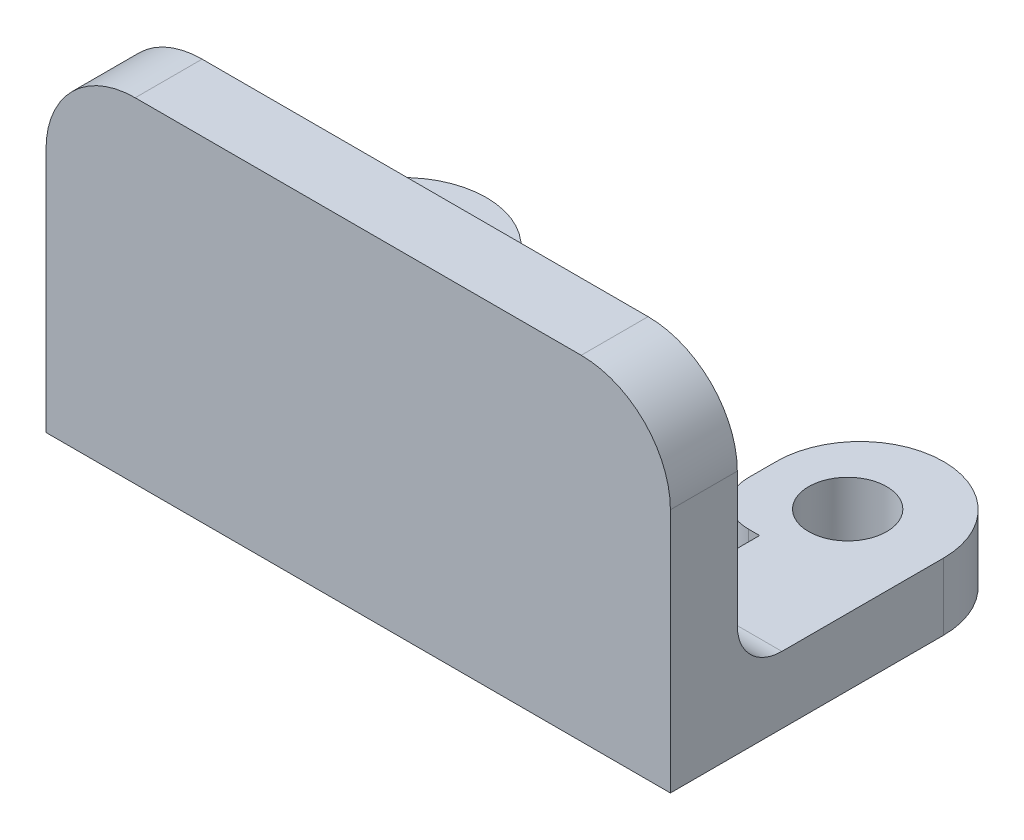
SolidWorks part; units mm, degrees
material "PP Copolymer"
ref_plane "Alzado" through (0, 0, 0) normal (0, 0, 1) x (1, 0, 0)
ref_plane "Planta" through (0, 0, 0) normal (0, 1, 0) x (1, 0, 0)
ref_plane "Vista lateral" through (0, 0, 0) normal (1, 0, 0) x (0, 0, -1)
sketch "Croquis2" plane through (0, 0, 0) normal (1, 0, 0) x (0, 0, -1)
  line L1 (-3, 1.5) -> (8, 1.5)
  line L2 (-8, 1.5) -> (-8, -1.5)
  line L3 (-8, -1.5) -> (8, -1.5)
  line L4 (8, 1.5) -> (8, -1.5)
  line L5 (-8, 1.5) -> (8, -1.5) construction
  line L6 (-8, -1.5) -> (8, 1.5) construction
  line L8 (-8, 1.5) -> (-8, 13.5)
  line L9 (-8, 13.5) -> (-5, 13.5)
  line L10 (-5, 3.5) -> (-5, 13.5)
  arc A0 (-5, 3.5) -> (-3, 1.5) centre (-3, 3.5) ccw
  point P0 (0, 0)
  dimension "D3" = 2
  dimension "D1" = 16
  dimension "D2" = 3
  dimension "D4" = 3
  dimension "D5" = 15
extrude "Saliente-Extruir1" add sketch "Croquis2" against normal mid plane 28
sketch "Croquis3" plane through (0, 1.5, 0) normal (0, 1, 0) x (1, 0, 0)
  line L2 (9, -2) -> (-9, -2)
  line L3 (-14, 8) -> (14, 8) construction
  line L4 (0, 8) -> (0, 4) construction
  line L5 (-9.95, 4) -> (9.95, 4) construction
  line L6 (0, 4) -> (0, -2) construction
  line L7 (6.5, 4.25) -> (6.5, 1)
  line L10 (-6.5, 8) -> (6.5, 8)
  line L11 (0, -1) -> (0, -2) construction
  line L12 (9, -2) -> (9, 1)
  line L13 (9, 1) -> (6.5, 1)
  line L16 (14, 8) -> (14, -3) construction
  line L17 (14, 4.25) -> (14, 8)
  line L18 (14, 8) -> (6.5, 8)
  line L19 (-14, 8) -> (-6.5, 8)
  line L20 (-14, 4.25) -> (-14, 8)
  line L21 (-9, 1) -> (-6.5, 1)
  line L22 (-9, -2) -> (-9, 1)
  line L23 (-6.5, 4.25) -> (-6.5, 1)
  circle A0 centre (9.95, 4) radius 1.75
  arc A4 (14, 4.25) -> (6.5, 4.25) centre (10.25, 4.25) ccw
  arc A5 (-14, 4.25) -> (-6.5, 4.25) centre (-10.25, 4.25) cw
  circle A6 centre (-9.95, 4) radius 1.75
  point P24 (-9, 1)
  line M7 (14, -3) -> (14, 8)
  line M8 (14, 8) -> (-14, 8)
  line M9 (-14, 8) -> (-14, -3)
  dimension "D2" = 19.9
  dimension "D3" = 10
  dimension "D4" = 4
extrude "Cortar-Extruir1" cut sketch "Croquis3" against normal blind 30 contours A5 L23 L21 L22 L2 L12 L13 L7 A4 L18 M8 | A4 M7 M8 | A5 L19 M9 | A0 | A6
fillet "Redondeo2" [suppressed] radius 4
fillet "Redondeo3" radius 4 2 edges at (-14, 13.5, 6.5) (14, 13.5, 6.5)
fillet "Redondeo4" radius 2 2 edges at (6.5, 0, -1) (-6.5, 0, -1)
